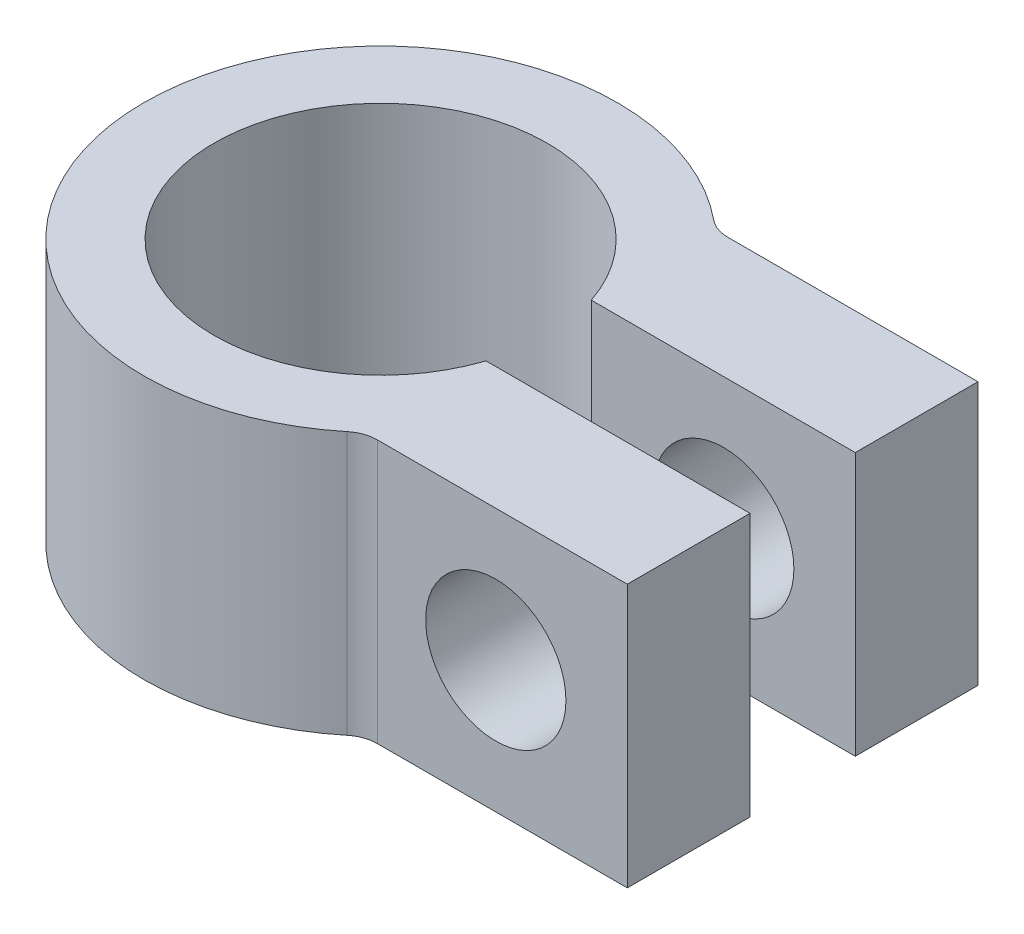
SolidWorks part; units mm, degrees
material "Manual Density from Real Component Anello di fissaggio 18 "
ref_plane "Piano frontale" through (0, 0, 0) normal (0, 0, 1) x (1, 0, 0)
ref_plane "Piano superiore" through (0, 0, 0) normal (0, 1, 0) x (1, 0, 0)
ref_plane "Piano destro" through (0, 0, 0) normal (1, 0, 0) x (0, 0, -1)
sketch "Schizzo3" plane through (0, 0, 0) normal (0, 1, 0) x (1, 0, 0)
  circle A0 centre (0, 0) radius 9.5
  circle A1 centre (0, 0) radius 13.5
  dimension "D1" = 27
  dimension "D2" = 19
extrude "Anello" add sketch "Schizzo3" along normal blind 15
sketch "Schizzo4" plane through (0, 0, 0) normal (0, 1, 0) x (1, 0, 0)
  line L0 (24.0692, 3) -> (13.1624, 3)
  line L3 (9.0692, 10) -> (24.0692, 10)
  line L4 (24.0692, 3) -> (24.0692, 10)
  circle A1 centre (0, 0) radius 13.5 construction
  arc A2 (9.0692, 10) -> (13.1624, 3) centre (0, 0) cw
  dimension "D1" = 7
  dimension "D2" = 15
  dimension "D3" = 3
extrude "AggancioAlto" add sketch "Schizzo4" along normal up to surface (15 mm away) up to face at (0, 15, 13.5)
mirror "AggancioBasso" about plane through (0, 0, 0) normal (0, 0, 1) of "AggancioAlto"
sketch "Schizzo5" plane through (0, 15, 0) normal (0, 1, 0) x (1, 0, 0)
  line L1 (0, 3) -> (24.0692, 3)
  line L2 (0, 3) -> (0, -3)
  line L3 (0, -3) -> (24.0692, -3)
  line L4 (24.0692, 3) -> (24.0692, -3)
  point P4 (0, 0)
extrude "AperturaAnello" cut sketch "Schizzo5" against normal through all
sketch "Schizzo6" plane through (0, 0, 10) normal (0, 0, 1) x (1, 0, 0)
  line L0 (24.0692, 15) -> (24.0692, 0) construction
  line L1 (24.0692, 15) -> (9.0692, 15) construction
  circle A0 centre (16.5692, 7.5) radius 4
  point P4 (24.0692, 7.5)
  point P8 (16.5692, 15)
  dimension "D1" = 8
extrude "ForoPassante" cut sketch "Schizzo6" against normal through all
fillet "RaccordoBasso" radius 2 1 edges at (9.0692, 7.5, 10)
fillet "RaccordoAlto" radius 2 1 edges at (9.0692, 7.5, -10)
